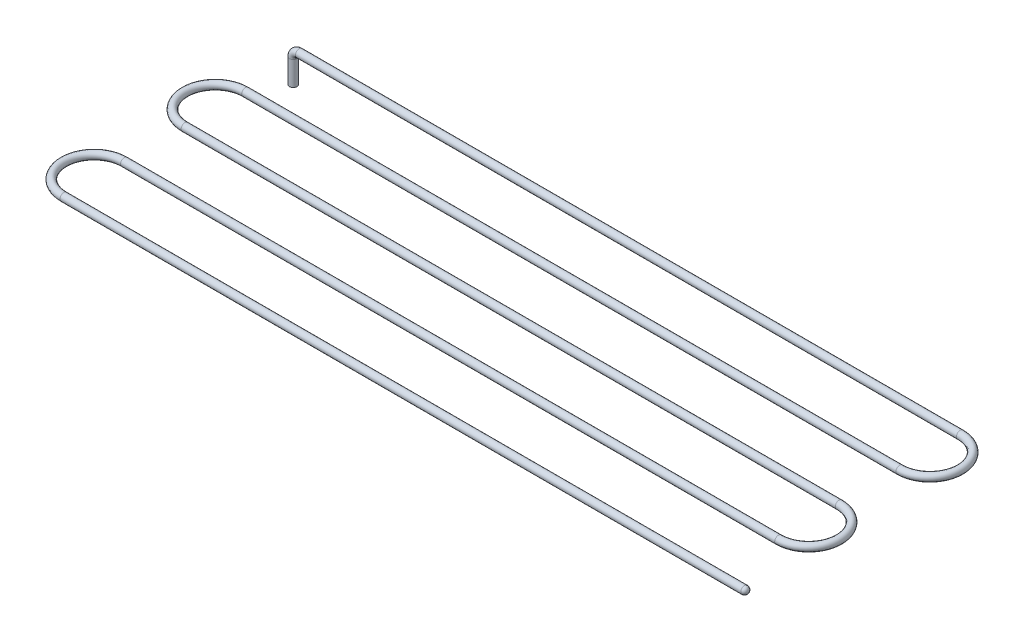
SolidWorks part; units mm, degrees
ref_plane "Plan de face" through (0, 0, 0) normal (0, 0, 1) x (1, 0, 0)
ref_plane "Plan de dessus" through (0, 0, 0) normal (0, 1, 0) x (1, 0, 0)
ref_plane "Plan de droite" through (0, 0, 0) normal (1, 0, 0) x (0, 0, -1)
sketch "Esquisse1" plane through (0, 0, 0) normal (0, 1, 0) x (1, 0, 0)
  line L0 (-19.994, 0) -> (546.8398, 0) construction
  line L1 (-19.994, 40) -> (546.8398, 40) construction
  line L2 (-19.994, 80) -> (546.8398, 80) construction
  line L3 (-19.994, 120) -> (546.8398, 120) construction
  line L4 (-19.994, 160) -> (546.8398, 160) construction
  line L5 (0, -18.821) -> (0, 210.6888) construction
  line L6 (472, -18.821) -> (472, 214.4021) construction
  line L7 (20, -18.821) -> (20, 192.7648) construction
  line L8 (452, -18.821) -> (452, 190.6837) construction
  line L9 (423.9379, 140) -> (502.9045, 140) construction
  line L10 (423.9379, 60) -> (502.9045, 60) construction
  line L11 (-19.994, 100) -> (30.857, 100) construction
  line L12 (-19.994, 20) -> (30.857, 20) construction
  line L13 (472, 0) -> (20, 0)
  line L14 (20, 40) -> (452, 40)
  line L15 (452, 80) -> (20, 80)
  line L16 (20, 120) -> (452, 120)
  line L17 (452, 160) -> (20, 160)
  arc A0 (20, 40) -> (20, 0) centre (20, 20) ccw
  arc A1 (20, 120) -> (20, 80) centre (20, 100) ccw
  arc A2 (452, 40) -> (452, 80) centre (452, 60) ccw
  arc A3 (452, 120) -> (452, 160) centre (452, 140) ccw
  dimension "D1" = 40
  dimension "D2" = 40
  dimension "D3" = 40
  dimension "D4" = 40
  dimension "D5" = 472
  dimension "D6" = 20
  dimension "D7" = 20
  dimension "D8" = 20
  dimension "D9" = 20
  dimension "D10" = 20
  dimension "D11" = 20
ref_plane "Plan1" through (472, 0, 0) normal (1, 0, 0) x (0, 0, -1)
sketch "Esquisse2" plane through (472, 0, 0) normal (1, 0, 0) x (0, 0, -1)
  circle A0 centre (0, 0) radius 2.5
sweep "Balayage1" add profiles "Esquisse2" path "Esquisse1"
fillet "Congé1" radius 2.4 1 edges at (472, 0, -2.5)
ref_plane "Plan2" through (0, 0, -160) normal (0, 0, 1) x (1, 0, 0)
sketch "Esquisse3" plane through (0, 0, -160) normal (0, 0, 1) x (1, 0, 0)
  line L0 (20, 0) -> (8.5657, 0) construction
  line L1 (20, 2.5) -> (20, -2.5) construction
  line L2 (11.5, -22.0838) -> (11.5, 6.3482) construction
  line L3 (20, -4.8055) -> (20, 6.3482) construction
  line L4 (8.5657, -20) -> (19.6707, -20) construction
  line L5 (20, 0) -> (15.5, 0)
  line L6 (11.5, -4) -> (11.5, -20)
  arc A0 (15.5, 0) -> (11.5, -4) centre (15.5, -4) ccw
  point P15 (11.5, 0)
  dimension "D3" = 4
  dimension "D1" = 8.5
  dimension "D2" = 20
sketch "Esquisse4" plane through (20, 0, 0) normal (-1, 0, 0) x (0, 0, 1)
  circle A0 centre (-160, 0) radius 2.5
sweep "Balayage2" add profiles "Esquisse4" path "Esquisse3"
